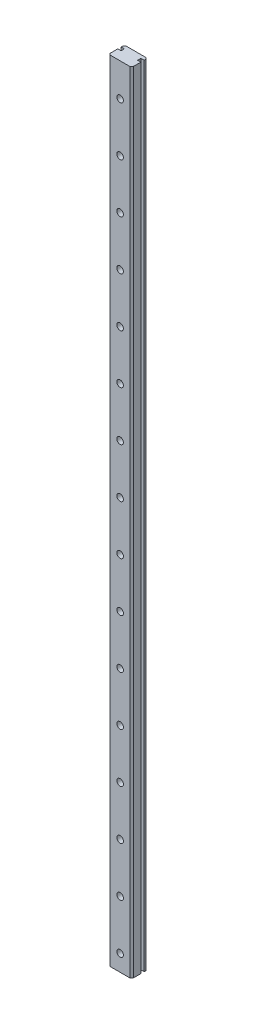
SolidWorks part; units mm, degrees
material "AISI 304"
ref_plane "前视基准面" through (0, 0, 0) normal (0, 0, 1) x (1, 0, 0)
ref_plane "上视基准面" through (0, 0, 0) normal (0, 1, 0) x (1, 0, 0)
ref_plane "右视基准面" through (0, 0, 0) normal (1, 0, 0) x (0, 0, -1)
other "Configuration Table"
sketch "草图1" plane through (0, 0, 0) normal (0, 1, 0) x (1, 0, 0)
  line L0 (0, 0) -> (0, 7.157) construction
  line L1 (-3.5, -2.4) -> (3.5, -2.4)
  line L2 (-3.5, -2.4) -> (-3.5, 2.4)
  line L3 (-3.5, 2.4) -> (3.5, 2.4)
  line L4 (3.5, -2.4) -> (3.5, 2.4)
  line L5 (-3.5, -2.4) -> (3.5, 2.4) construction
  line L6 (-3.5, 2.4) -> (3.5, -2.4) construction
  line L7 (3.5, 1.4) -> (2.5, 1.4)
  line L8 (2.5, 1.4) -> (2.5, 0.4)
  line L9 (2.5, 0.4) -> (3.5, 0.4)
  line L10 (-2.5, 0.4) -> (-3.5, 0.4)
  line L11 (-2.5, 1.4) -> (-2.5, 0.4)
  line L12 (-3.5, 1.4) -> (-2.5, 1.4)
  point P0 (0, 0)
  dimension "D1" = 7
  dimension "D2" = 4.8
  dimension "D3" = 1
  dimension "D4" = 1
  dimension "D5" = 1
extrude "凸台-拉伸1" add sketch "草图1" along normal blind 240 contours L2 L12 L11 L10 L1 L4 L9 L8 L7 L3
sketch "草图2" plane through (0, 0, -2.4) normal (0, 0, -1) x (-1, 0, 0)
  line L0 (3.5, 0) -> (-3.5, 0) construction
  line L1 (-3.5, 240) -> (-3.5, 0) construction
  circle A0 centre (0, 5) radius 1
  circle A1 centre (0, 20) radius 1
  circle A2 centre (0, 35) radius 1
  circle A3 centre (0, 50) radius 1
  circle A4 centre (0, 65) radius 1
  circle A5 centre (0, 80) radius 1
  circle A6 centre (0, 95) radius 1
  circle A7 centre (0, 110) radius 1
  circle A8 centre (0, 125) radius 1
  circle A9 centre (0, 140) radius 1
  circle A10 centre (0, 155) radius 1
  circle A11 centre (0, 170) radius 1
  circle A12 centre (0, 185) radius 1
  circle A13 centre (0, 200) radius 1
  circle A14 centre (0, 215) radius 1
  circle A15 centre (0, 230) radius 1
  dimension "D1" = 2
  dimension "D2" = 5
  dimension "D5" = 15
  dimension "D3" = 3.5
  dimension "D4" = 16
extrude "切除-拉伸1" cut sketch "草图2" against normal blind 10
chamfer "倒角1" distance 0.5 angle 45 4 edges at (-3.5, 120, 2.4) (3.5, 120, 2.4) (-3.5, 120, -2.4) (3.5, 120, -2.4)
sketch "草图3" plane through (0, 0, -2.4) normal (0, 0, -1) x (-1, 0, 0)
  circle A0 centre (0, 5) radius 2.3833
  circle A1 centre (0, 20) radius 2.3833
  circle A2 centre (0, 35) radius 2.3833
  circle A3 centre (0, 50) radius 2.3833
  circle A4 centre (0, 65) radius 2.3833
  circle A5 centre (0, 80) radius 2.3833
  circle A6 centre (0, 95) radius 2.3833
  circle A7 centre (0, 110) radius 2.3833
  circle A8 centre (0, 125) radius 2.3833
  circle A9 centre (0, 140) radius 2.3833
  circle A10 centre (0, 155) radius 2.3833
  circle A11 centre (0, 170) radius 2.3833
  circle A12 centre (0, 185) radius 2.3833
  circle A13 centre (0, 200) radius 2.3833
  circle A14 centre (0, 215) radius 2.3833
  circle A15 centre (0, 230) radius 2.3833
  dimension "D1" = 4.7666
  dimension "D3" = 15
  dimension "D2" = 16
extrude "切除-拉伸2" cut sketch "草图3" against normal blind 1
